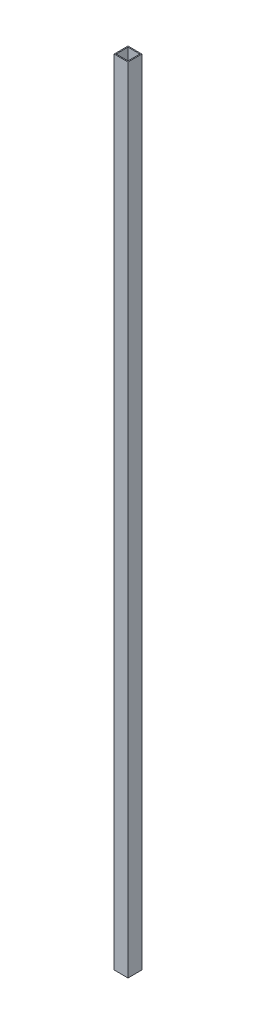
SolidWorks part; units mm, degrees
ref_plane "Front Plane" through (0, 0, 0) normal (0, 0, 1) x (1, 0, 0)
ref_plane "Top Plane" through (0, 0, 0) normal (0, 1, 0) x (1, 0, 0)
ref_plane "Right Plane" through (0, 0, 0) normal (1, 0, 0) x (0, 0, -1)
sketch "Sketch1" plane through (0, 0, 0) normal (0, 1, 0) x (1, 0, 0)
  line L0 (-1, -1) -> (-13, -1)
  line L1 (0, 0) -> (-14, 0)
  line L2 (0, 0) -> (0, -14)
  line L3 (0, -14) -> (-14, -14)
  line L4 (-14, 0) -> (-14, -14)
  line L5 (-13, -1) -> (-13, -13)
  line L6 (-1, -13) -> (-13, -13)
  line L7 (-1, -1) -> (-1, -13)
  dimension "D1" = 14
  dimension "D2" = 14
  dimension "D3" = 1
extrude "Boss-Extrude1" add sketch "Sketch1" along normal blind 800 contours L4 L3 L2 L1 | L5 L6 L7 L0
